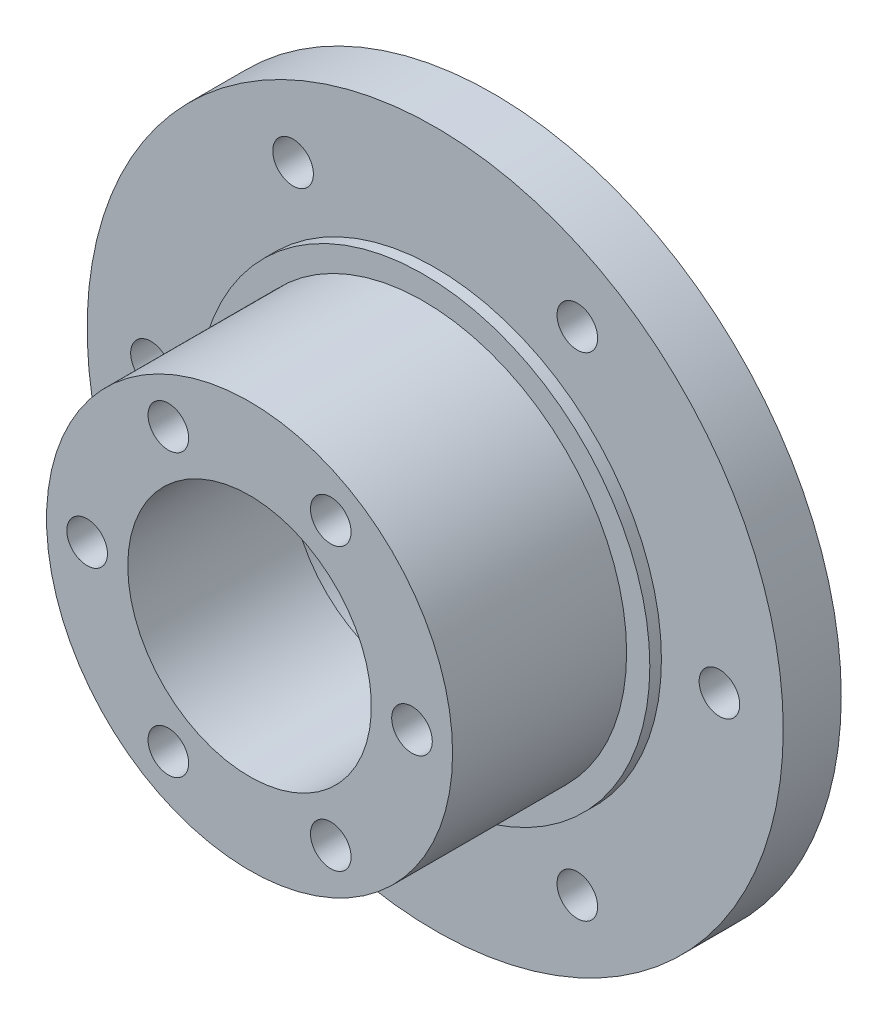
SolidWorks part; units mm, degrees
ref_plane "Front Plane" through (0, 0, 0) normal (0, 0, 1) x (1, 0, 0)
ref_plane "Top Plane" through (0, 0, 0) normal (0, 1, 0) x (1, 0, 0)
ref_plane "Right Plane" through (0, 0, 0) normal (1, 0, 0) x (0, 0, -1)
sketch "Sketch1" plane through (0, 0, 0) normal (0, 0, 1) x (1, 0, 0)
  circle A0 centre (0, 0) radius 30
  dimension "D1" = 60
extrude "Boss-Extrude1" add sketch "Sketch1" along normal blind 5
sketch "Sketch2" plane through (0, 0, 5) normal (0, 0, 1) x (1, 0, 0)
  circle A0 centre (0, 0) radius 19.5
  dimension "D1" = 39
extrude "Boss-Extrude2" add sketch "Sketch2" along normal blind 1
sketch "Sketch3" plane through (0, 0, 6) normal (0, 0, 1) x (1, 0, 0)
  circle A0 centre (0, 0) radius 17.5
  dimension "D1" = 35
extrude "Boss-Extrude3" add sketch "Sketch3" along normal blind 15
sketch "Sketch4" plane through (0, 0, 0) normal (0, 0, -1) x (-1, 0, 0)
  circle A0 centre (0, 0) radius 12.025
  dimension "D1" = 24.05
extrude "Cut-Extrude1" cut sketch "Sketch4" against normal blind 7 contours A0
sketch "Sketch5" plane through (0, 0, 7) normal (0, 0, -1) x (-1, 0, 0)
  circle A0 centre (0, 0) radius 10.5
  dimension "D1" = 21
extrude "Cut-Extrude2" cut sketch "Sketch5" against normal through all
sketch "Sketch6" plane through (0, 0, 5) normal (0, 0, 1) x (1, 0, 0)
  line L0 (0, 0) -> (33.6942, 0) construction
  circle A0 centre (0, 0) radius 24.5 construction
  circle A1 centre (24.5, 0) radius 1.75
  circle A2 centre (12.25, -21.2176) radius 1.75
  circle A3 centre (-12.25, -21.2176) radius 1.75
  circle A4 centre (-24.5, 0) radius 1.75
  circle A5 centre (-12.25, 21.2176) radius 1.75
  circle A6 centre (12.25, 21.2176) radius 1.75
  point P19 (0, 0)
  dimension "D1" = 49
  dimension "D2" = 3.5
  dimension "D3" = 6
extrude "Cut-Extrude3" cut sketch "Sketch6" against normal through all
sketch "Sketch7" plane through (0, 0, 21) normal (0, 0, 1) x (1, 0, 0)
  line L0 (0, 0) -> (34.5762, 0) construction
  circle A0 centre (0, 0) radius 14 construction
  circle A3 centre (14, 0) radius 1.75
  circle A5 centre (7, -12.1244) radius 1.75
  circle A6 centre (-7, -12.1244) radius 1.75
  circle A7 centre (-14, 0) radius 1.75
  circle A8 centre (-7, 12.1244) radius 1.75
  circle A9 centre (7, 12.1244) radius 1.75
  point P20 (0, 0)
  dimension "D1" = 28
  dimension "D2" = 3.5
  dimension "D3" = 6
extrude "Cut-Extrude4" cut sketch "Sketch7" against normal blind 12
